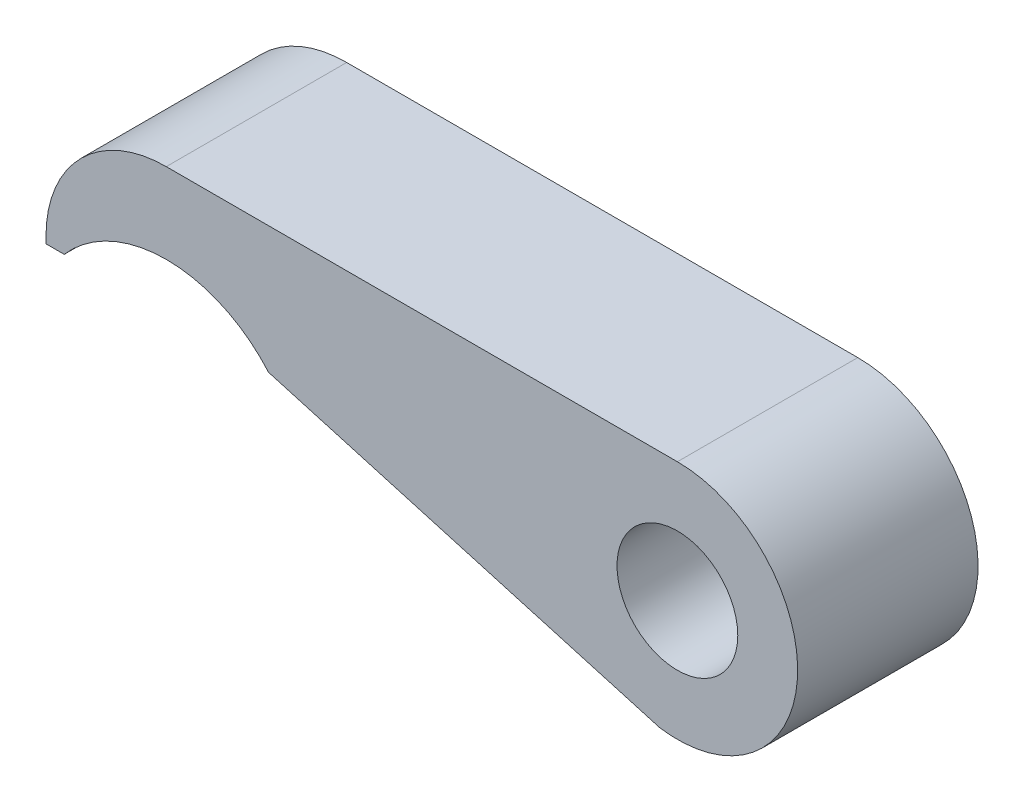
SolidWorks part; units mm, degrees
ref_plane "Front" through (0, 0, 0) normal (0, 0, 1) x (1, 0, 0)
ref_plane "Top" through (0, 0, 0) normal (0, 1, 0) x (1, 0, 0)
ref_plane "Right" through (0, 0, 0) normal (1, 0, 0) x (0, 0, -1)
sketch "Sketch1" plane through (0, 0, 0) normal (0, 0, 1) x (1, 0, 0)
  line L0 (-19.8438, -1.016) -> (19.8437, -1.016) construction
  line L1 (-19.8438, -5.6896) -> (19.8437, -5.6896) construction
  line L2 (-19.8438, -5.6896) -> (-19.8438, 5.6896) construction
  line L3 (-19.8438, 5.6896) -> (19.8437, 5.6896) construction
  line L4 (19.8437, -5.6896) -> (19.8437, 5.6896) construction
  line L5 (-19.8438, -5.6896) -> (19.8437, 5.6896) construction
  line L6 (-19.8438, 5.6896) -> (19.8437, -5.6896) construction
  line L7 (-13.4874, -5.6896) -> (-13.4874, -1.016) construction
  line L8 (-13.4874, -1.016) -> (13.4874, -1.016) construction
  line L9 (13.4874, 5.6896) -> (13.4874, -5.6896) construction
  line L10 (-19.8438, -1.016) -> (-18.8818, -1.016)
  line L11 (-19.8438, -1.016) -> (-19.8438, -0.6604)
  line L12 (-13.4938, 5.6896) -> (13.4937, 5.6896)
  line L13 (-8.093, -1.016) -> (12.5831, -6.9448)
  arc A0 (12.5831, -6.9448) -> (10.9358, -6.4724) centre (13.4937, -0.6604) ccw construction
  circle A1 centre (-13.4874, -5.6896) radius 7.1374 construction
  arc A2 (-18.8818, -1.016) -> (-8.093, -1.016) centre (-13.4874, -5.6896) cw
  arc A3 (13.4937, 5.6896) -> (12.5831, -6.9448) centre (13.4937, -0.6604) cw
  arc A4 (-19.8438, -0.6604) -> (-13.4938, 5.6896) centre (-13.4938, -0.6604) cw
  circle A5 centre (13.4937, -0.6604) radius 3.1877
  point P0 (0, 0)
  point P13 (0, -1.016)
  dimension "D4" = 12.7
  dimension "D5" = 14.2748
  dimension "D7" = 6.35
  dimension "D8" = 16
  dimension "D9" = 6.3754
  dimension "D1" = 11.3792
  dimension "D2" = 39.6875
  dimension "D3" = 6.7056
  dimension "D6" = 26.9748
extrude "Boss-Extrude1" add sketch "Sketch1" against normal blind 9.525
